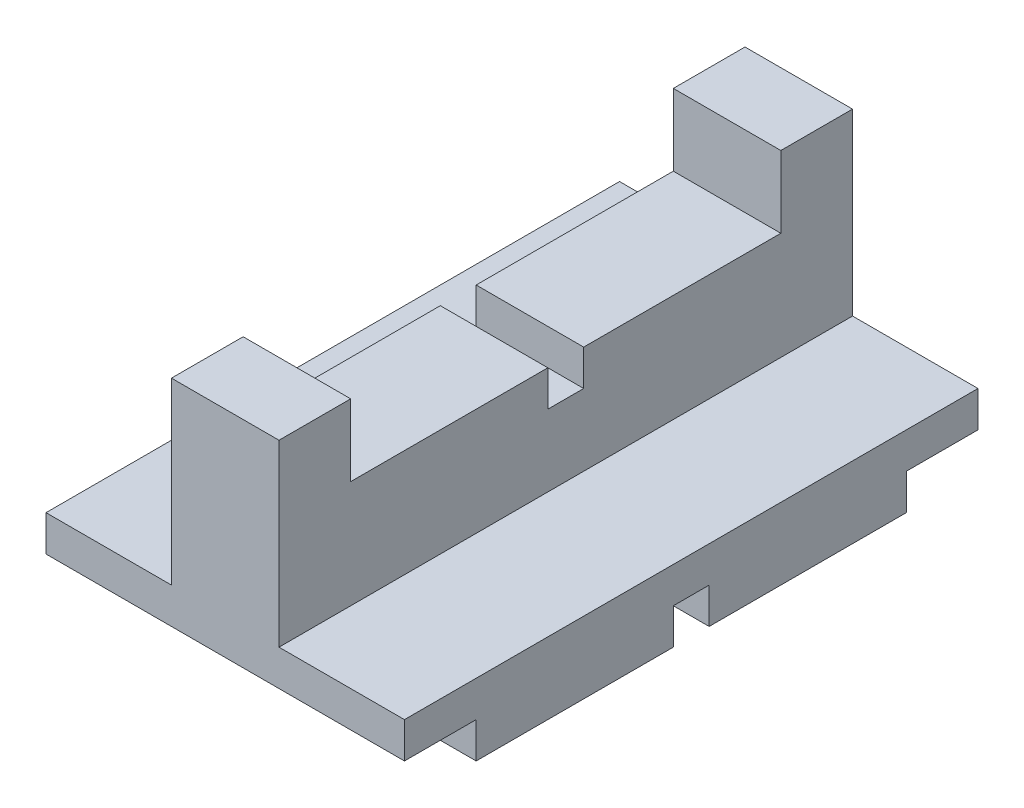
SolidWorks part; units mm, degrees
ref_plane "Front Plane" through (0, 0, 0) normal (0, 0, 1) x (1, 0, 0)
ref_plane "Top Plane" through (0, 0, 0) normal (0, 1, 0) x (1, 0, 0)
ref_plane "Right Plane" through (0, 0, 0) normal (1, 0, 0) x (0, 0, -1)
sketch "Sketch1" plane through (0, 0, 0) normal (0, 0, 1) x (1, 0, 0)
  line L0 (-7.8607, 0) -> (-25.3607, 0)
  line L1 (-7.8607, 0) -> (-7.8607, 25)
  line L2 (-7.8607, 25) -> (7.1393, 25)
  line L3 (7.1393, 25) -> (7.1393, 0)
  line L4 (-25.3607, 0) -> (-25.3607, -10)
  line L5 (-25.3607, -10) -> (24.6393, -10)
  line L6 (24.6393, -10) -> (24.6393, 0)
  line L7 (24.6393, 0) -> (7.1393, 0)
  dimension "D1" = 15
  dimension "D2" = 25
  dimension "D3" = 17.5
  dimension "D4" = 50
  dimension "D5" = 10
extrude "Boss-Extrude1" add sketch "Sketch1" along normal blind 80
sketch "Sketch4" plane through (7.1393, 0, 0) normal (1, 0, 0) x (0, 0, -1)
  line L5 (-80, 25) -> (0, 25) construction
  line L10 (-37.5, 10) -> (-42.5, 10)
  line L12 (-70, 25) -> (-10, 25)
  line L13 (-70, 25) -> (-70, 15)
  line L14 (-70, 15) -> (-10, 15)
  line L15 (-10, 25) -> (-10, 15)
  line L18 (-37.5, 10) -> (-37.5, 15)
  line L20 (-42.5, 15) -> (-42.5, 10)
extrude "Cut-Extrude1" cut sketch "Sketch4" against normal through all contours L14 L15 L12 L13
sketch "Sketch6" plane through (7.1393, 0, 0) normal (1, 0, 0) x (0, 0, -1)
  line L0 (-37.4998, 10) -> (0, 10)
  line L11 (0, 0) -> (0, 25) construction
  line L12 (-42.4998, 9.9663) -> (-80, 9.9663)
  line L13 (-80, 0) -> (-80, 25) construction
  line L14 (-70, 15) -> (-10, 15) construction
  line L15 (-37.4998, 10) -> (-42.4998, 10)
  line L16 (-37.4998, 10) -> (-37.4998, 15)
  line L17 (-37.4998, 15) -> (-42.4998, 15)
  line L18 (-42.4998, 10) -> (-42.4998, 15)
sketch "Sketch9" plane through (24.6393, 0, 0) normal (1, 0, 0) x (0, 0, -1)
  line L0 (-80, -10) -> (-80, 0) construction
  line L1 (-80, -5) -> (0, -5)
  line L2 (0, -10) -> (0, 0) construction
  line L3 (-70, 15) -> (-70, -5)
  line L5 (-80, -10) -> (0, -10) construction
  line L6 (-80, -5) -> (-70, -5)
  line L7 (-80, -5) -> (-80, -10)
  line L8 (-80, -10) -> (-70, -10)
  line L9 (-70, -5) -> (-70, -10)
extrude "Cut-Extrude6" cut sketch "Sketch9" against normal through all contours L7 L6 L9 L8
sketch "Sketch10" plane through (24.6393, 0, 0) normal (1, 0, 0) x (0, 0, -1)
  line L0 (-10, 15) -> (-10, -10)
  line L1 (-70, -10) -> (0, -10) construction
  line L2 (-70, -5) -> (-10, -5)
  line L4 (-10, -5) -> (0, -5)
  line L5 (-10, -5) -> (-10, -10)
  line L6 (-10, -10) -> (0, -10)
  line L7 (0, -5) -> (0, -10)
extrude "Cut-Extrude7" cut sketch "Sketch10" against normal through all contours L5 L4 L7 L6
sketch "Sketch12" plane through (24.6393, 0, 0) normal (1, 0, 0) x (0, 0, -1)
  line L2 (-70, -10) -> (-10, -10) construction
  line L5 (-42.4998, -10) -> (-37.4998, -10)
  line L6 (-42.4998, -10) -> (-42.4998, -5)
  line L7 (-42.4998, -5) -> (-37.4998, -5)
  line L8 (-37.4998, -10) -> (-37.4998, -5)
extrude "Cut-Extrude9" cut sketch "Sketch12" against normal through all contours L6 L5 L8 L7
extrude "Cut-Extrude11" cut sketch "Sketch6" against normal through all contours L16 L15 L18 L17
